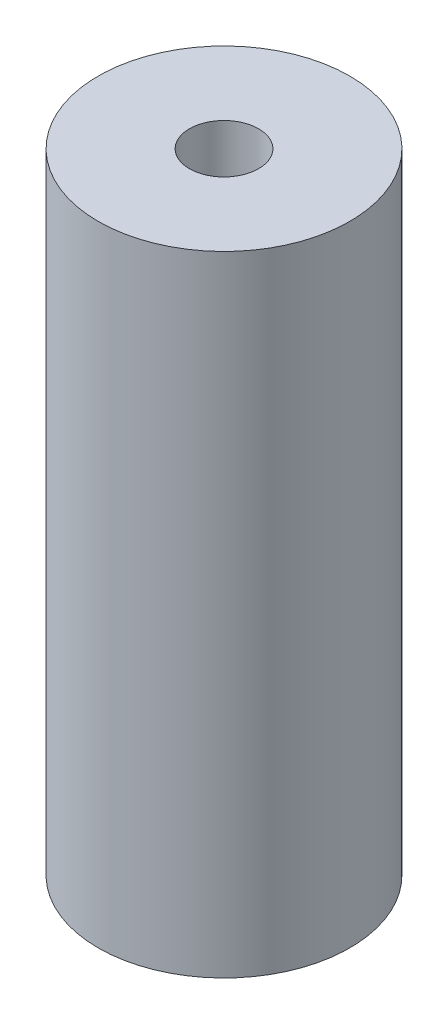
SolidWorks part; units mm, degrees
ref_plane "前视基准面" through (0, 0, 0) normal (0, 0, 1) x (1, 0, 0)
ref_plane "上视基准面" through (0, 0, 0) normal (0, 1, 0) x (1, 0, 0)
ref_plane "右视基准面" through (0, 0, 0) normal (1, 0, 0) x (0, 0, -1)
sketch "草图1" plane through (0, 0, 0) normal (0, 1, 0) x (1, 0, 0)
  circle A0 centre (0, 0) radius 6
extrude "凸台-拉伸1" add sketch "草图1" along normal blind 30
sketch "草图2" plane through (0, 0, 0) normal (0, -1, 0) x (-1, 0, 0)
  point P0 (0, 0)
hole_wizard "M4 螺纹孔1" positions "草图2" profile "草图3" tap size "M4" standard "DIN" end condition through all
sketch "草图3" plane through (0, 0, 0) normal (1, 0, 0) x (0, 0, -1)
  line L0 (0, 0) -> (0, 30)
  line L1 (0, 30) -> (1.65, 30)
  line L2 (1.65, 30) -> (1.65, 0.375)
  line L3 (1.65, 0.375) -> (2.025, 0)
  line L5 (2.025, 0) -> (0, 0)
  line L6 (-1.65, 0.375) -> (-2.025, 0) construction
  line L11 (0, -6.35) -> (0, 107.95) construction
  dimension "通孔螺纹孔钻头直径" = 3.3
  dimension "通孔螺纹孔钻头深度" = 30
  dimension "近端锥形沉头孔直径" = 4.05
  dimension "近端锥形沉头孔角度" = 90
cosmetic thread "孔螺纹线1" parameters "D2"=4
